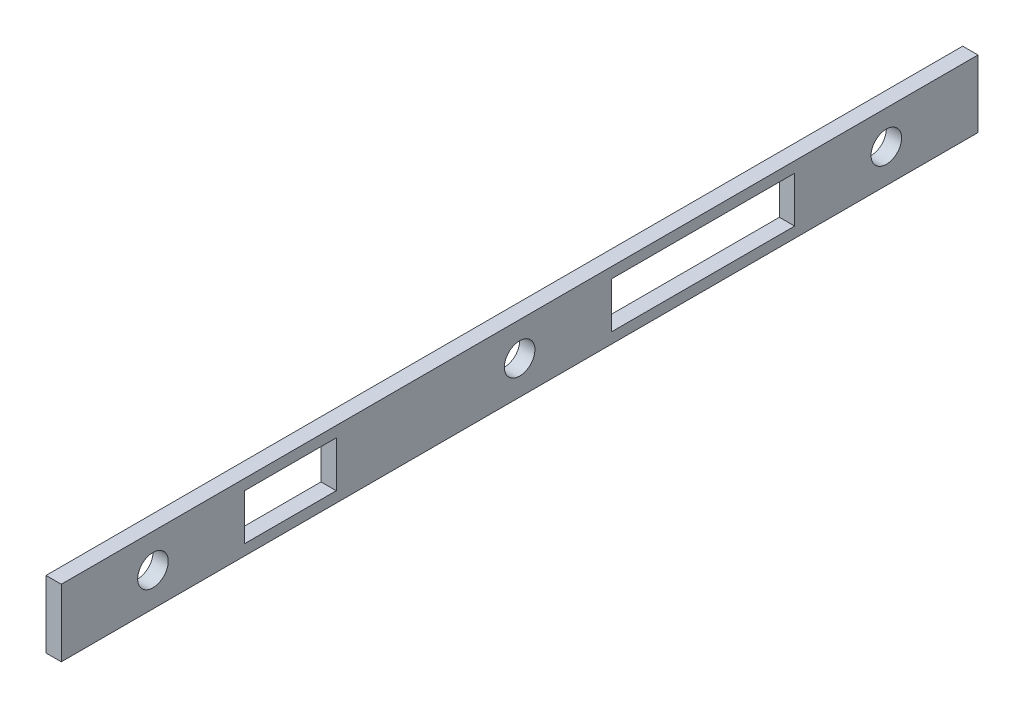
SolidWorks part; units mm, degrees
ref_plane "Front Plane" through (0, 0, 0) normal (0, 0, 1) x (1, 0, 0)
ref_plane "Top Plane" through (0, 0, 0) normal (0, 1, 0) x (1, 0, 0)
ref_plane "Right Plane" through (0, 0, 0) normal (1, 0, 0) x (0, 0, -1)
sketch "Sketch1" plane through (0, 0, 0) normal (1, 0, 0) x (0, 0, -1)
  line L1 (0, 0) -> (300, 0)
  line L2 (0, 0) -> (0, 22)
  line L3 (0, 22) -> (300, 22)
  line L4 (300, 0) -> (300, 22)
  dimension "D1" = 22
  dimension "D2" = 300
extrude "Boss-Extrude1" add sketch "Sketch1" along normal blind 5
sketch "Sketch2" plane through (5, 0, 0) normal (1, 0, 0) x (0, 0, -1)
  line L0 (300, 22) -> (0, 22) construction
  line L1 (0, 22) -> (0, 0) construction
  line L2 (300, 0) -> (300, 22) construction
  line L3 (0, 0) -> (300, 0) construction
  line L4 (60, 18.5) -> (90, 18.5)
  line L5 (60, 18.5) -> (60, 3.5)
  line L6 (60, 3.5) -> (90, 3.5)
  line L7 (90, 18.5) -> (90, 3.5)
  line L8 (180, 18.5) -> (240, 18.5)
  line L9 (180, 18.5) -> (180, 3.5)
  line L10 (180, 3.5) -> (240, 3.5)
  line L11 (240, 18.5) -> (240, 3.5)
  circle A0 centre (30, 11) radius 5
  circle A1 centre (150, 11) radius 5
  circle A2 centre (270, 11) radius 5
  dimension "D1" = 10
  dimension "D2" = 10
  dimension "D3" = 10
  dimension "D7" = 30
  dimension "D8" = 150
  dimension "D9" = 30
  dimension "D4" = 11
  dimension "D5" = 11
  dimension "D6" = 11
  dimension "D10" = 30
  dimension "D11" = 30
  dimension "D12" = 15
  dimension "D13" = 15
  dimension "D14" = 30
  dimension "D15" = 30
  dimension "D16" = 3.5
  dimension "D17" = 3.5
extrude "Cut-Extrude1" cut sketch "Sketch2" against normal blind 5
